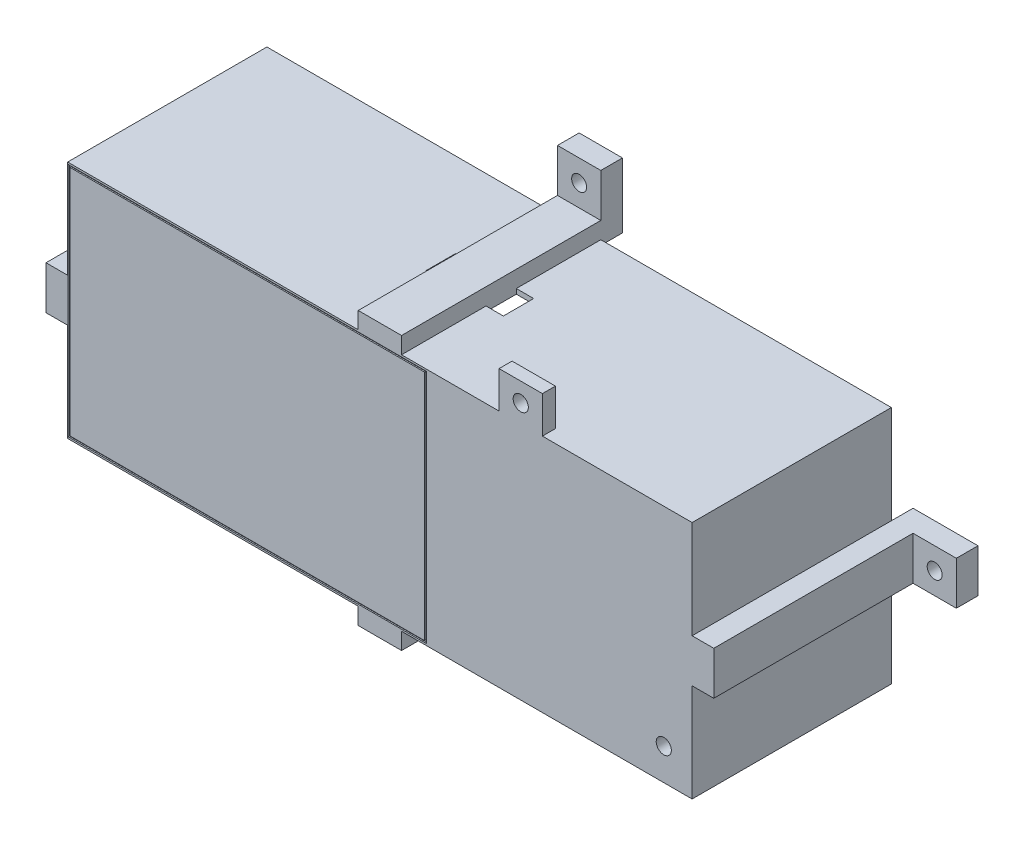
SolidWorks part; units mm, degrees
ref_plane "Front Plane" through (0, 0, 0) normal (0, 0, 1) x (1, 0, 0)
ref_plane "Top Plane" through (0, 0, 0) normal (0, 1, 0) x (1, 0, 0)
ref_plane "Right Plane" through (0, 0, 0) normal (1, 0, 0) x (0, 0, -1)
sketch "Sketch2" plane through (0, 0, 0) normal (0, 0, 1) x (1, 0, 0)
  line L0 (-68.085, -22.5) -> (68.085, 22.5) construction
  line L1 (-68.085, 22.5) -> (68.085, 22.5) construction
  line L2 (-68.085, 22.5) -> (-68.085, -22.5) construction
  line L3 (-68.085, -22.5) -> (68.085, -22.5) construction
  line L4 (68.085, 22.5) -> (68.085, -22.5) construction
  line L5 (-72.085, 26.5) -> (72.085, 26.5) construction
  line L6 (72.085, 26.5) -> (72.085, -26.5) construction
  line L7 (-72.085, -26.5) -> (72.085, -26.5) construction
  line L8 (-72.085, 26.5) -> (-72.085, -26.5) construction
  line L9 (0, 0) -> (-100, 0) construction
  line L10 (-77.085, 5) -> (-72.085, 5)
  line L11 (-77.085, 5) -> (-77.085, -5)
  line L12 (-77.085, -5) -> (-72.085, -5)
  line L13 (-72.085, 5) -> (-72.085, -5)
  line L14 (-5, 31.5) -> (5, 31.5)
  line L15 (-5, 31.5) -> (-5, 26.5)
  line L16 (-5, 26.5) -> (5, 26.5)
  line L17 (5, 31.5) -> (5, 26.5)
  line L18 (0, 0) -> (0, 108.7377) construction
  line L19 (-77.085, 5) -> (-72.085, -5) construction
  line L20 (-5, 26.5) -> (5, 31.5) construction
  line L21 (77.085, -5) -> (72.085, -5)
  line L22 (77.085, 5) -> (77.085, -5)
  line L23 (72.085, 5) -> (72.085, -5)
  line L24 (77.085, 5) -> (72.085, 5)
  line L25 (-5, -26.5) -> (5, -26.5)
  line L26 (-5, -31.5) -> (-5, -26.5)
  line L27 (-5, -31.5) -> (5, -31.5)
  line L28 (5, -31.5) -> (5, -26.5)
  point P4 (0, 0)
  point P23 (-74.585, 0)
  point P25 (0, 29)
  dimension "D1" = 45
  dimension "D2" = 136.17
  dimension "D4" = 5
  dimension "D5" = 10
  dimension "D6" = 5
  dimension "D7" = 10
  dimension "D3" = 4
extrude "Boss-Extrude1" add sketch "Sketch2" along normal blind 48
sketch "Sketch3" plane through (0, 0, 48) normal (0, 0, 1) x (1, 0, 0)
  line L0 (-82.5, 27.64) -> (82.5, -27.64) construction
  line L1 (-82.5, 27.64) -> (82.5, 27.64)
  line L2 (-82.5, 27.64) -> (-82.5, -27.64)
  line L3 (-82.5, -27.64) -> (82.5, -27.64)
  line L4 (82.5, 27.64) -> (82.5, -27.64)
  point P4 (0, 0)
  dimension "D1" = 165
  dimension "D2" = 55.28
extrude "Boss-Extrude2" add sketch "Sketch3" along normal blind 3
sketch "Sketch4" plane through (0, 0, 48) normal (0, 0, 1) x (1, 0, 0)
  line L0 (-5, 27.64) -> (5, 27.64) construction
  line L1 (5, 27.64) -> (5, 31.5) construction
  line L2 (5, 31.5) -> (-5, 31.5) construction
  line L3 (-5, 31.5) -> (-5, 27.64) construction
  line L4 (5, -31.5) -> (5, -27.64) construction
  line L5 (5, -27.64) -> (-5, -27.64) construction
  line L6 (-5, -27.64) -> (-5, -31.5) construction
  line L7 (-5, -31.5) -> (5, -31.5) construction
  line L8 (-5, 27.64) -> (5, 27.64)
  line L9 (5, 27.64) -> (5, 31.5)
  line L10 (5, 31.5) -> (-5, 31.5)
  line L11 (-5, 31.5) -> (-5, 27.64)
  line L12 (5, -31.5) -> (5, -27.64)
  line L13 (5, -27.64) -> (-5, -27.64)
  line L14 (-5, -27.64) -> (-5, -31.5)
  line L15 (-5, -31.5) -> (5, -31.5)
extrude "Boss-Extrude3" add sketch "Sketch4" along normal up to surface (3 mm away) up to face at (0, 0, 51)
sketch "Sketch5" plane through (0, 5, 0) normal (0, 1, 0) x (1, 0, 0)
  line L0 (0, 0) -> (0, -40.7206) construction
  line L1 (-77.085, 0) -> (-87.085, 0)
  line L2 (-77.085, 0) -> (-77.085, -5)
  line L3 (-77.085, -5) -> (-87.085, -5)
  line L4 (-87.085, 0) -> (-87.085, -5)
  line L5 (87.085, 0) -> (87.085, -5)
  line L6 (77.085, 0) -> (87.085, 0)
  line L7 (77.085, 0) -> (77.085, -5)
  line L8 (77.085, -5) -> (87.085, -5)
  dimension "D1" = 5
  dimension "D2" = 10
extrude "Boss-Extrude4" add sketch "Sketch5" against normal up to surface (10 mm away) up to face at (-74.585, -5, 24)
sketch "Sketch7" plane through (-5, 0, 0) normal (-1, 0, 0) x (0, 0, 1)
  line L0 (0, 0) -> (45.7182, 0) construction
  line L1 (0, 31.5) -> (5, 31.5)
  line L2 (0, 31.5) -> (0, 41.5)
  line L3 (0, 41.5) -> (5, 41.5)
  line L4 (5, 31.5) -> (5, 41.5)
  line L5 (0, -41.5) -> (5, -41.5)
  line L6 (0, -31.5) -> (0, -41.5)
  line L7 (0, -31.5) -> (5, -31.5)
  line L8 (5, -31.5) -> (5, -41.5)
  dimension "D1" = 5
  dimension "D2" = 10
extrude "Boss-Extrude5" add sketch "Sketch7" against normal up to surface (10 mm away) up to face at (5, -28.5467, 33)
sketch "Sketch8" plane through (0, 0, 5) normal (0, 0, 1) x (1, 0, 0)
  line L0 (-87.085, 5) -> (-77.085, -5) construction
  line L1 (-5, -31.5) -> (5, -41.5) construction
  line L2 (0, 0) -> (0, 49.5906) construction
  line L3 (0, 0) -> (57.6811, 0) construction
  circle A0 centre (-82.085, 0) radius 1.73
  circle A1 centre (0, -36.5) radius 1.73
  circle A2 centre (82.085, 0) radius 1.73
  circle A3 centre (0, 36.5) radius 1.73
  dimension "D1" = 3.46
  dimension "D2" = 3.46
extrude "Cut-Extrude1" cut sketch "Sketch8" against normal through all
sketch "Metro Express Layout Reference" plane through (0, 0, 51) normal (0, 0, 1) x (1, 0, 0)
  line L0 (0.32, 27.64) -> (0.32, -27.64) construction
  line L1 (14.74, 34.29) -> (68.08, 34.29) construction
  line L2 (14.74, 34.29) -> (14.74, -34.29) construction
  line L3 (14.74, -34.29) -> (68.08, -34.29) construction
  line L4 (68.08, 34.29) -> (68.08, -34.29) construction
  line L5 (82.5, -27.64) -> (82.5, 27.64) construction
  line L7 (-5, 27.64) -> (-82.5, 27.64) construction
  line L8 (-82.5, -27.64) -> (-5, -27.64) construction
  line L9 (-82.5, 27.64) -> (-82.5, -27.64) construction
  circle A0 centre (32.52, 31.75) radius 1.75 construction
  circle A1 centre (65.54, -20.32) radius 1.75 construction
  point P4 (68.08, 0)
  point P7 (82.5, 0)
  dimension "D5" = 3.5
  dimension "D7" = 3.5
  dimension "D1" = 68.58
  dimension "D2" = 53.34
  dimension "D3" = 17.78
  dimension "D4" = 2.54
  dimension "D6" = 13.97
  dimension "D8" = 2.54
  dimension "D9" = 82.82
  dimension "D10" = 14.42
sketch "Sketch10" plane through (0, 0, 51) normal (0, 0, 1) x (1, 0, 0)
  line L0 (82.5, 27.64) -> (5, 27.64) construction
  line L1 (27.52, 27.64) -> (37.52, 27.64)
  line L2 (27.52, 27.64) -> (27.52, 36.14)
  line L3 (27.52, 36.14) -> (37.52, 36.14)
  line L4 (37.52, 27.64) -> (37.52, 36.14)
  line L5 (68.08, 34.29) -> (68.08, -34.29) construction
  line L6 (68.08, -15.32) -> (69.93, -15.32)
  line L7 (68.08, -15.32) -> (68.08, -25.32)
  line L8 (68.08, -25.32) -> (69.93, -25.32)
  line L9 (69.93, -15.32) -> (69.93, -25.32)
  point P6 (32.52, 27.64)
  point P14 (68.08, -20.32)
  dimension "D1" = 8.5
  dimension "D2" = 10
  dimension "D3" = 10
  dimension "D4" = 4.39
extrude "Boss-Extrude6" add sketch "Sketch10" against normal up to surface (3 mm away) up to face at (74.585, 0, 48)
sketch "Sketch11" plane through (0, 0, 51) normal (0, 0, 1) x (1, 0, 0)
  circle A0 centre (32.52, 31.75) radius 1.75
  circle A1 centre (65.54, -20.32) radius 1.75
  circle A2 centre (32.52, 31.75) radius 1.75 construction
  circle A3 centre (65.54, -20.32) radius 1.75 construction
extrude "Cut-Extrude3" cut sketch "Sketch11" against normal through all
sketch "Sketch12" plane through (0, 0, 51) normal (0, 0, 1) x (1, 0, 0)
  line L0 (-82.5, 27.64) -> (-82.5, -27.64) construction
  line L1 (-71.785, 27.03) -> (10.535, 27.03) construction
  line L2 (-71.785, 27.03) -> (-71.785, -27.03) construction
  line L3 (-71.785, -27.03) -> (10.535, -27.03) construction
  line L4 (10.535, 27.03) -> (10.535, -27.03) construction
  line L5 (-71.985, 27.23) -> (-71.985, -27.23)
  line L6 (-12.815, 8.88) -> (12.815, 8.88) construction
  line L7 (-12.815, 8.88) -> (-12.815, -8.88) construction
  line L8 (-12.815, -8.88) -> (12.815, -8.88) construction
  line L9 (12.815, 8.88) -> (12.815, -8.88) construction
  line L10 (-71.985, -27.23) -> (10.735, -27.23)
  line L11 (10.735, 27.23) -> (10.735, -27.23)
  line L12 (-71.985, 27.23) -> (10.735, 27.23)
  line L13 (-71.585, 26.83) -> (-71.585, -26.83)
  line L14 (-71.585, -26.83) -> (10.335, -26.83)
  line L15 (10.335, 26.83) -> (10.335, -26.83)
  line L16 (-71.585, 26.83) -> (10.335, 26.83)
  point P4 (12.815, 0)
  point P5 (-71.785, 0)
  point P8 (-82.5, 0)
  point P15 (0, 8.88)
  dimension "D1" = 82.32
  dimension "D2" = 54.06
  dimension "D3" = 25.63
  dimension "D4" = 17.76
  dimension "D5" = 2.28
  dimension "D6" = 0.2
  dimension "D7" = 0.2
extrude "Cut-Extrude4" cut sketch "Sketch12" against normal blind 0.28
sketch "Sketch13" plane through (0, 0, 48) normal (0, 0, -1) x (-1, 0, 0)
  line L0 (82.5, -27.64) -> (82.5, 27.64)
  line L5 (-82.5, 27.64) -> (-82.5, -27.64)
  line L17 (-82.5, 27.64) -> (-37.52, 27.64) construction
  line L18 (-82.5, -27.64) -> (-72.085, -27.64)
  line L20 (-77.085, -5) -> (-72.085, -5)
  line L21 (-72.085, -27.64) -> (-72.085, -5)
  line L25 (-77.085, -5) -> (-77.085, 5)
  line L26 (-77.085, 5) -> (-72.085, 5)
  line L28 (-82.5, 27.64) -> (-72.085, 27.64)
  line L29 (-72.085, 5) -> (-72.085, 27.64)
  line L30 (5, 27.64) -> (82.5, 27.64) construction
  line L31 (82.5, -27.64) -> (72.085, -27.64)
  line L33 (77.085, -5) -> (72.085, -5)
  line L34 (72.085, -27.64) -> (72.085, -5)
  line L38 (77.085, -5) -> (77.085, 5)
  line L39 (77.085, 5) -> (72.085, 5)
  line L41 (82.5, 27.64) -> (72.085, 27.64)
  line L42 (72.085, 5) -> (72.085, 27.64)
extrude "Cut-Extrude5" cut sketch "Sketch13" against normal through all
sketch "Sketch14" plane through (0, 0, 48) normal (0, 0, -1) x (-1, 0, 0)
  line L0 (72.085, -5) -> (72.085, -27.64) construction
  line L1 (-72.085, 27.64) -> (-37.52, 27.64) construction
  line L2 (-27.52, 27.64) -> (-5, 27.64) construction
  line L3 (-72.085, 5) -> (-72.085, 27.64) construction
  line L4 (-5, -27.64) -> (-72.085, -27.64) construction
  line L6 (72.085, -27.64) -> (5, -27.64) construction
  line L10 (72.085, 27.64) -> (72.085, 5) construction
  line L11 (5, 27.64) -> (72.085, 27.64) construction
  line L15 (-72.085, -27.64) -> (-72.085, -5) construction
  line L157 (72.085, -5) -> (72.085, 5) construction
  line L158 (-72.085, 5) -> (-72.085, -5) construction
  line L159 (72.085, -27.64) -> (5, -27.64)
  line L160 (72.085, -5) -> (72.085, -27.64)
  line L161 (72.085, -5) -> (72.085, 5)
  line L162 (72.085, 27.64) -> (72.085, 5)
  line L163 (5, 27.64) -> (72.085, 27.64)
  line L164 (-72.085, 5) -> (-72.085, -5)
  line L165 (-72.085, -27.64) -> (-72.085, -5)
  line L166 (-5, -27.64) -> (-72.085, -27.64)
  line L167 (-72.085, 5) -> (-72.085, 27.64)
  line L168 (-27.52, 27.64) -> (-5, 27.64)
  line L169 (-72.085, 27.64) -> (-37.52, 27.64)
  line L170 (-5, -26.5) -> (-70.945, -26.5)
  line L171 (-70.945, -26.5) -> (-70.945, -5)
  line L172 (-70.945, 5) -> (-70.945, -5)
  line L173 (-70.945, 5) -> (-70.945, 26.5)
  line L174 (-70.945, 26.5) -> (-37.52, 26.5)
  line L175 (-27.52, 26.5) -> (-5, 26.5)
  line L176 (5, 26.5) -> (70.945, 26.5)
  line L177 (70.945, 26.5) -> (70.945, 5)
  line L178 (70.945, -5) -> (70.945, 5)
  line L179 (70.945, -5) -> (70.945, -26.5)
  line L180 (70.945, -26.5) -> (5, -26.5)
  line L181 (-37.52, 27.64) -> (-27.52, 27.64)
  line L182 (-37.52, 26.5) -> (-27.52, 26.5)
  line L183 (-5, -26.5) -> (-5, -27.64)
  line L184 (5, -26.5) -> (5, -27.64)
  line L185 (-5, 27.64) -> (-5, 26.5)
  line L186 (5, 27.64) -> (5, 26.5)
  dimension "D1" = 1.14
extrude "Boss-Extrude7" add sketch "Sketch14" along normal up to surface (43 mm away) up to face at (80.355, 0, 5)
sketch "Sketch15" plane through (0, 0, 5) normal (0, 0, -1) x (-1, 0, 0)
  line L0 (72.085, -17.64) -> (70.945, -17.64)
  line L1 (72.085, -5) -> (72.085, -27.64) construction
  line L2 (70.945, -26.5) -> (70.945, 26.5) construction
  line L3 (70.945, -17.64) -> (70.945, -26.5)
  line L4 (5, -26.5) -> (70.945, -26.5) construction
  line L5 (70.945, -26.5) -> (62.085, -26.5)
  line L6 (62.085, -26.5) -> (62.085, -27.64)
  line L7 (72.085, -27.64) -> (5, -27.64) construction
  line L8 (62.085, -27.64) -> (72.085, -27.64)
  line L9 (72.085, -27.64) -> (72.085, -17.64)
  dimension "D1" = 10
  dimension "D2" = 10
extrude "Cut-Extrude6" cut sketch "Sketch15" against normal blind 33.5
sketch "Sketch16" plane through (0, -27.64, 0) normal (0, -1, 0) x (1, 0, 0)
  line L0 (5, 51) -> (5, 5) construction
  line L1 (5, 38) -> (9, 38)
  line L2 (5, 38) -> (5, 31)
  line L3 (5, 31) -> (9, 31)
  line L4 (9, 38) -> (9, 31)
  line L5 (70.945, 48) -> (-70.945, 48) construction
  line L6 (5, 17) -> (9, 17)
  line L7 (5, 17) -> (5, 10)
  line L8 (5, 10) -> (9, 10)
  line L9 (9, 17) -> (9, 10)
  line L10 (5, 5) -> (72.085, 5) construction
  line L11 (0, 0) -> (0, 45.8798) construction
  line L12 (-5, 17) -> (-5, 10)
  line L13 (-5, 10) -> (-9, 10)
  line L14 (-9, 17) -> (-9, 10)
  line L15 (-5, 17) -> (-9, 17)
  line L16 (-5, 31) -> (-9, 31)
  line L17 (-5, 38) -> (-5, 31)
  line L18 (-9, 38) -> (-9, 31)
  line L19 (-5, 38) -> (-9, 38)
  dimension "D1" = 7
  dimension "D2" = 7
  dimension "D3" = 4
  dimension "D4" = 4
  dimension "D5" = 10
  dimension "D6" = 5
extrude "Cut-Extrude7" cut sketch "Sketch16" against normal up to surface (1.14 mm away) up to face at (-12.417, -26.5, 19.3)
sketch "Sketch17" plane through (0, 27.64, 0) normal (0, 1, 0) x (1, 0, 0)
  line L0 (5, -51) -> (5, -5) construction
  line L1 (5, -24.5) -> (9, -24.5)
  line L2 (5, -24.5) -> (5, -31.5)
  line L3 (5, -31.5) -> (9, -31.5)
  line L4 (9, -24.5) -> (9, -31.5)
  line L5 (0, 0) -> (0, -41.863) construction
  line L6 (5, 0) -> (-5, 0) construction
  line L7 (72.085, -28) -> (24.4078, -28) construction
  line L8 (72.085, -51) -> (72.085, -5) construction
  line L9 (-5, -24.5) -> (-5, -31.5)
  line L10 (-5, -31.5) -> (-9, -31.5)
  line L11 (-9, -24.5) -> (-9, -31.5)
  line L12 (-5, -24.5) -> (-9, -24.5)
  point P14 (9, -28)
  dimension "D1" = 7
  dimension "D2" = 4
extrude "Cut-Extrude8" cut sketch "Sketch17" against normal up to surface (1.14 mm away) up to face at (0, 26.5, 14.5)
